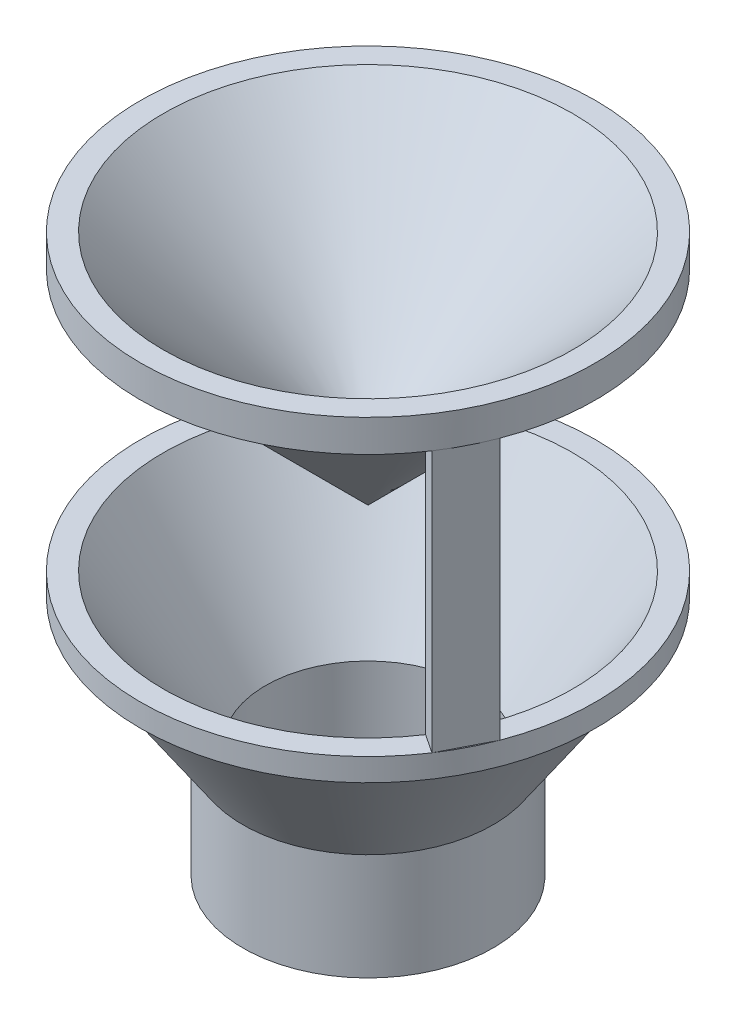
SolidWorks part; units mm, degrees
ref_plane "Front Plane" through (0, 0, 0) normal (0, 0, 1) x (1, 0, 0)
ref_plane "Top Plane" through (0, 0, 0) normal (0, 1, 0) x (1, 0, 0)
ref_plane "Right Plane" through (0, 0, 0) normal (1, 0, 0) x (0, 0, -1)
sketch "Sketch1" plane through (0, 0, 0) normal (0, 0, 1) x (1, 0, 0)
  line L0 (-9, 0) -> (-9, -10)
  line L1 (-9, 0) -> (-18, 13.2288)
  line L2 (-18, 13.2288) -> (-20, 13.2288)
  line L3 (0, 0) -> (0, 17.3566) construction
  point P0 (-9, 0)
  dimension "D1" = 9
  dimension "D2" = 10
  dimension "D3" = 16
  dimension "D4" = 9
  dimension "D5" = 2
revolve "Revolve-Thin3" add sketch "Sketch1" angle 360 about L3
sketch "Sketch7" plane through (0, 0, 0) normal (0, 0, 1) x (1, 0, 0)
  line L0 (0, 0) -> (0, 44.7266) construction
  line L1 (18, 13.2288) -> (18, 64.8856) construction
  line L2 (18, 13.2288) -> (-18, 13.2288) construction
  line L3 (0, 18.2288) -> (18, 36.2288)
  line L4 (18, 36.2288) -> (20, 36.2288)
  line L5 (20, 36.2288) -> (20, 39.0572)
  line L6 (20, 39.0572) -> (18, 39.0572)
  line L7 (18, 39.0572) -> (0, 21.0572)
  line L8 (0, 21.0572) -> (0, 18.2288)
  point P6 (0, 18.2288)
  dimension "D1" = 5
  dimension "D2" = 2
  dimension "D3" = 2
revolve "Revolve2" add sketch "Sketch7" angle 360 about L0
sketch "Sketch8" plane through (0, 36.2288, 0) normal (0, -1, 0) x (1, 0, 0)
  line L0 (-16.0244, -8.1987) -> (16.0156, 8.2159) construction
  line L1 (-16.0244, -8.1987) -> (-16.899, -6.1987)
  line L2 (-16.0244, -8.1987) -> (-15.0159, -9.9259)
  line L3 (-16.899, -6.1987) -> (-18.7766, -6.8875)
  line L4 (-15.0159, -9.9259) -> (-16.6843, -11.0287)
  line L5 (-16.6843, -11.0287) -> (-18.7766, -6.8875)
  line L6 (16.0156, 8.2159) -> (15.0052, 9.942)
  line L7 (16.0156, 8.2159) -> (16.8282, 6.3884)
  line L8 (15.0052, 9.942) -> (16.6725, 11.0466)
  line L9 (16.8282, 6.3884) -> (18.698, 7.0983)
  line L10 (18.698, 7.0983) -> (16.6725, 11.0466)
  circle A0 centre (0, 0) radius 18 construction
  circle A1 centre (0, 0) radius 20 construction
  dimension "D1" = 2
  dimension "D2" = 2
  dimension "D3" = 2
  dimension "D4" = 2
extrude "Boss-Extrude2" add sketch "Sketch8" along normal blind 23
